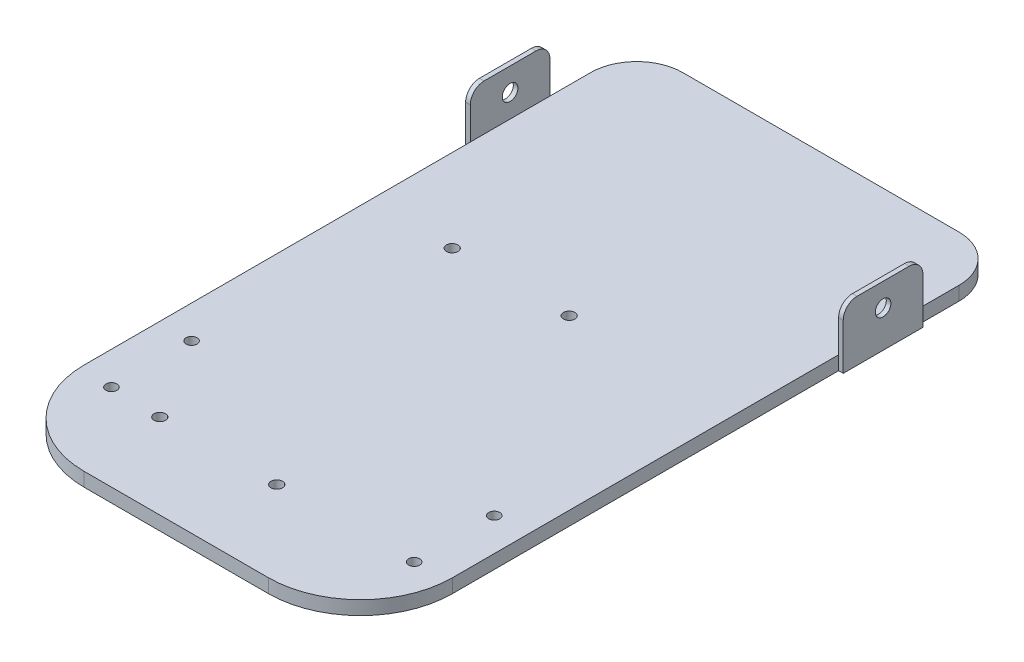
SolidWorks part; units mm, degrees
ref_plane "정면" through (0, 0, 0) normal (0, 0, 1) x (1, 0, 0)
ref_plane "윗면" through (0, 0, 0) normal (0, 1, 0) x (1, 0, 0)
ref_plane "우측면" through (0, 0, 0) normal (1, 0, 0) x (0, 0, -1)
sketch "스케치1" plane through (0, 0, 0) normal (0, 1, 0) x (1, 0, 0)
  line L0 (0, -53.23) -> (0, 51.0623) construction
  line L1 (40, -35.2285) -> (-40, -35.2285)
  line L2 (-40, -35.2285) -> (-40, -16.3785)
  line L3 (-40, 104.7715) -> (40, 104.7715)
  line L7 (-40, 68.6215) -> (-41, 68.6215)
  line L8 (-41, 68.6215) -> (-41, 85.9215)
  line L9 (-41, 85.9215) -> (-40, 85.9215)
  line L10 (-41, 77.2715) -> (41, 77.2715) construction
  line L11 (-46, -7.7285) -> (46, -7.7285) construction
  line L12 (-40, 85.9215) -> (-40, 104.7715)
  line L13 (-40, -16.3785) -> (-40, 68.6215)
  line L14 (40, -16.3785) -> (40, 68.6215)
  line L15 (40, 85.9215) -> (40, 104.7715)
  line L16 (41, 85.9215) -> (40, 85.9215)
  line L17 (41, 68.6215) -> (41, 85.9215)
  line L18 (40, 68.6215) -> (41, 68.6215)
  line L22 (40, -35.2285) -> (40, -16.3785)
  point P20 (0, -7.7285)
  point P21 (0, 77.2715)
  point P30 (0, 104.7715)
  point P31 (0, -35.2285)
  dimension "D1" = 140
  dimension "D2" = 80
  dimension "D3" = 17.3
  dimension "D5" = 85
  dimension "D7" = 1
extrude "보스-돌출1" add sketch "스케치1" against normal blind 3
fillet "필렛1" radius 20 1 edges at (-40, -1.5, 35.2285)
fillet "필렛2" radius 20 1 edges at (40, -1.5, 35.2285)
fillet "필렛3" radius 10 2 edges at (40, -1.5, -104.7715) (-40, -1.5, -104.7715)
sketch "스케치2" plane through (0, 0, 0) normal (0, 1, 0) x (1, 0, 0)
  line L3 (-40, 68.6215) -> (-40, -15.2285) construction
  line L4 (-20, -35.2285) -> (20, -35.2285) construction
  circle A0 centre (-32.87, -16.4285) radius 1.2
  circle A1 centre (-32.87, 0.9715) radius 1.2
  dimension "D1" = 18.8
  dimension "D2" = 7.13
extrude "컷-돌출1" cut sketch "스케치2" against normal through all
mirror "대칭 복사1" about plane through (0, 0, 0) normal (1, 0, 0) of "컷-돌출1"
sketch "스케치5" plane through (0, 0, 0) normal (0, 1, 0) x (1, 0, 0)
  line L1 (-41, 85.9215) -> (-40, 85.9215)
  line L2 (-41, 85.9215) -> (-41, 68.6215)
  line L3 (-41, 68.6215) -> (-40, 68.6215)
  line L4 (-40, 85.9215) -> (-40, 68.6215)
extrude "보스-돌출2" add sketch "스케치5" along normal blind 10
sketch "스케치7" plane through (-40, 0, 0) normal (1, 0, 0) x (0, 0, -1)
  line L0 (68.6215, 0) -> (85.9215, 0) construction
  line L1 (85.9215, 10) -> (85.9215, 0) construction
  circle A0 centre (77.2715, 5) radius 1.7
  dimension "D1" = 5
  dimension "D2" = 8.65
extrude "컷-돌출2" cut sketch "스케치7" against normal through all
fillet "필렛4" radius 3 2 edges at (-40.5, 10, -68.6215) (-40.5, 10, -85.9215)
mirror "대칭 복사3" about plane through (0, 0, 0) normal (1, 0, 0) of "컷-돌출2", "필렛4", "보스-돌출2"
hole_wizard "M3 탭을 위한 탭 드릴1" positions "스케치11" profile "스케치10" hole size "M3" standard "Ks"
sketch "스케치11" plane through (0, 0, 0) normal (0, 1, 0) x (1, 0, 0)
  line L0 (-40, 68.6215) -> (-40, -15.2285) construction
  point P0 (-22, -16.8002)
  point P2 (3.4, -16.8002)
  point P4 (3.4, 46.6998)
  point P6 (-22, 46.6998)
  dimension "D1" = 63.5
  dimension "D2" = 25.4
  dimension "D3" = 18
  dimension "D4" = 25.4
  dimension "D5" = 63.5
sketch "스케치10" plane through (-22, 0, 16.8002) normal (1, 0, 0) x (0, 0, 1)
  line L0 (0, 0) -> (0, 3.7511)
  line L1 (0, 3.7511) -> (1.25, 3)
  line L2 (1.25, 3) -> (1.25, 0)
  line L5 (1.25, 0) -> (0, 0)
  line L10 (0, 3.7511) -> (-1.25, 3) construction
  line L11 (0, -6.35) -> (0, 107.95) construction
  dimension "구멍 지름" = 2.5
  dimension "구멍 깊이" = 3
  dimension "드릴 각도" = 118
